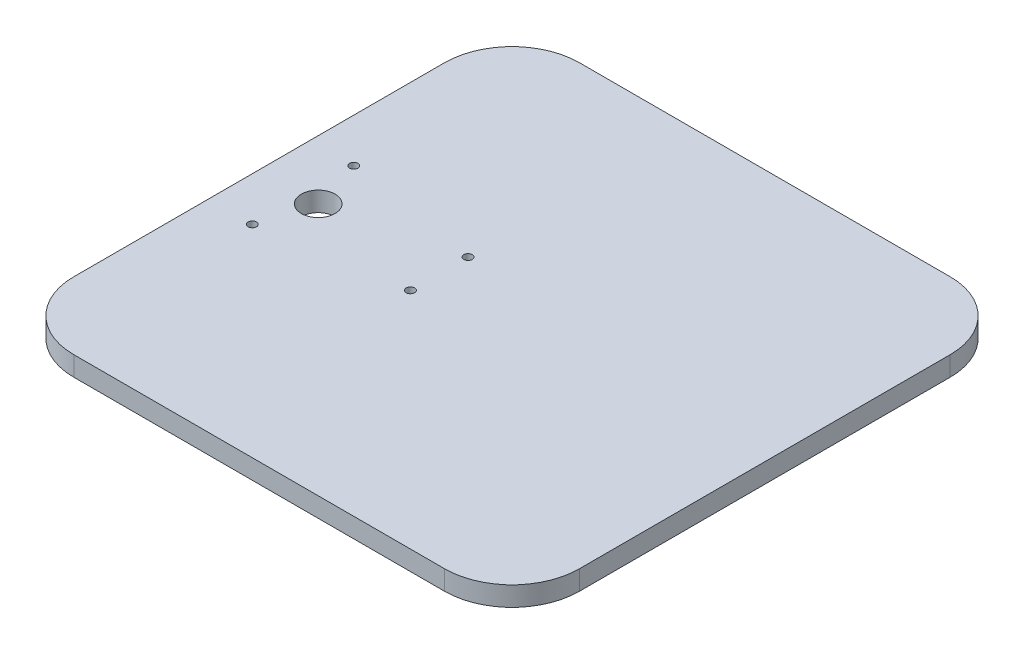
SolidWorks part; units mm, degrees
ref_plane "Front Plane" through (0, 0, 0) normal (0, 0, 1) x (1, 0, 0)
ref_plane "Top Plane" through (0, 0, 0) normal (0, 1, 0) x (1, 0, 0)
ref_plane "Right Plane" through (0, 0, 0) normal (1, 0, 0) x (0, 0, -1)
sketch "Sketch1" plane through (0, 0, 0) normal (0, 1, 0) x (1, 0, 0)
  line L1 (75, -75) -> (-75, -75)
  line L2 (75, -75) -> (75, 75)
  line L3 (75, 75) -> (-75, 75)
  line L4 (-75, -75) -> (-75, 75)
  line L5 (75, -75) -> (-75, 75) construction
  line L6 (75, 75) -> (-75, -75) construction
  point P0 (0, 0)
  dimension "D1" = 150
  dimension "D2" = 150
extrude "Boss-Extrude1" add sketch "Sketch1" along normal blind 5.8
sketch "Sketch2" plane through (0, 5.8, 0) normal (0, 1, 0) x (1, 0, 0)
  line L0 (-20.9607, 0) -> (-66.5864, 0) construction
  circle A0 centre (-61.9857, -15.05) radius 1.25
  circle A1 centre (-61.9857, 15.05) radius 1.25
  circle A2 centre (-21.5857, 8.55) radius 1.25
  circle A3 centre (-21.5857, -8.55) radius 1.25
  circle A4 centre (-57.4857, 0) radius 5
  dimension "D1" = 2.5
  dimension "D4" = 2.5
  dimension "D5" = 2.5
  dimension "D8" = 10
  dimension "D2" = 15.05
  dimension "D3" = 15.05
  dimension "D6" = 8.55
  dimension "D7" = 40.4
  dimension "D9" = 4.5
extrude "Cut-Extrude1" cut sketch "Sketch2" against normal through all both and the other way through all
fillet "Fillet1" radius 20 4 edges at (75, 2.9, -75) (75, 2.9, 75) (-75, 2.9, 75) (-75, 2.9, -75)
sketch "Sketch3" plane through (0, 0, 0) normal (0, -1, 0) x (1, 0, 0)
  circle A2 centre (-21.5857, -8.55) radius 6.25
  circle A3 centre (-21.5857, -8.55) radius 6.25
  circle A5 centre (-21.5857, 8.55) radius 6.25
  circle A6 centre (-21.5857, 8.55) radius 6.25
  circle A8 centre (-61.9857, -15.05) radius 6.25
  circle A9 centre (-61.9857, -15.05) radius 6.25
  circle A11 centre (-61.9857, 15.05) radius 6.25
  circle A12 centre (-61.9857, 15.05) radius 6.25
  dimension "D1" = 5
  dimension "D2" = 5
  dimension "D3" = 5
  dimension "D4" = 5
extrude "Cut-Extrude2" cut sketch "Sketch3" against normal blind 3.5
